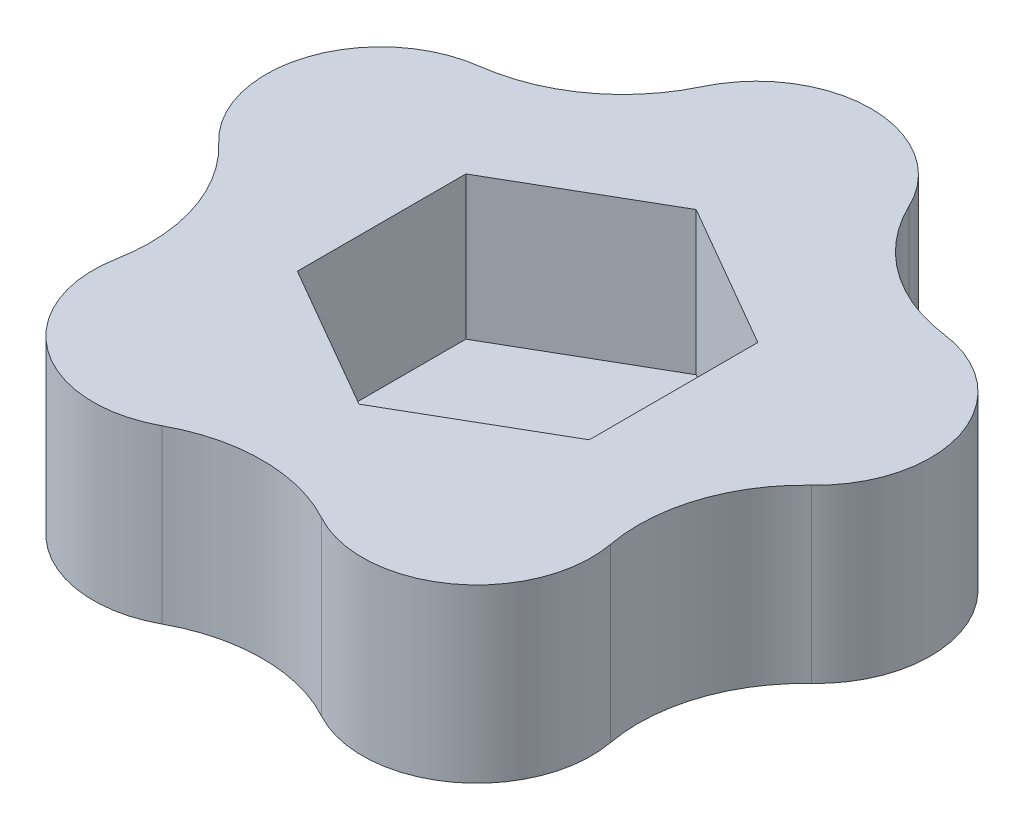
SolidWorks part; units mm, degrees
ref_plane "Front Plane" through (0, 0, 0) normal (0, 0, 1) x (1, 0, 0)
ref_plane "Top Plane" through (0, 0, 0) normal (0, 1, 0) x (1, 0, 0)
ref_plane "Right Plane" through (0, 0, 0) normal (1, 0, 0) x (0, 0, -1)
sketch "Sketch1" plane through (0, 0, 0) normal (0, 1, 0) x (1, 0, 0)
  line L0 (0, 0) -> (0, 8) construction
  line L1 (0, 8) -> (0, 13.848) construction
  line L2 (0, 5.889) -> (-5.1, 2.9445) construction
  line L3 (-5.1, 2.9445) -> (-5.1, -2.9445) construction
  line L4 (-5.1, -2.9445) -> (0, -5.889) construction
  line L5 (0, -5.889) -> (5.1, -2.9445) construction
  line L6 (5.1, -2.9445) -> (5.1, 2.9445) construction
  line L7 (5.1, 2.9445) -> (0, 5.889) construction
  circle A0 centre (0, 0) radius 5.1 construction
  arc A1 (-3.6141, 9.7142) -> (3.6141, 9.7142) centre (0, 8) cw
  arc A2 (8.122, 6.439) -> (10.3556, -0.4353) centre (7.6085, 2.4721) cw
  arc A3 (8.6337, -5.7347) -> (2.786, -9.9833) centre (4.7023, -6.4721) cw
  arc A4 (-2.786, -9.9833) -> (-8.6337, -5.7347) centre (-4.7023, -6.4721) cw
  arc A5 (-10.3556, -0.4353) -> (-8.122, 6.439) centre (-7.6085, 2.4721) cw
  arc A6 (-3.6141, 9.7142) -> (-8.122, 6.439) centre (-8.8686, 12.2066) cw
  arc A7 (8.122, 6.439) -> (3.6141, 9.7142) centre (8.8686, 12.2066) cw
  arc A8 (8.6337, -5.7347) -> (10.3556, -0.4353) centre (14.3497, -4.6625) cw
  arc A9 (-2.786, -9.9833) -> (2.786, -9.9833) centre (0, -15.0882) cw
  arc A10 (-10.3556, -0.4353) -> (-8.6337, -5.7347) centre (-14.3497, -4.6625) cw
  point P14 (0, 0)
  point P18 (0, 7.2098)
  point P28 (0, 0)
  point P41 (0, 0)
  dimension "D4" = 4
  dimension "D1" = 10.2
  dimension "D5" = 8
  dimension "D2" = 5
  dimension "D3" = 5
extrude "Boss-Extrude1" add sketch "Sketch1" along normal blind 6
sketch "Sketch2" plane through (0, 6, 0) normal (0, 1, 0) x (1, 0, 0)
  line L0 (-5.1, 2.9445) -> (-5.1, -2.9445) construction
  line L1 (-5.1, -2.9445) -> (0, -5.889) construction
  line L2 (0, -5.889) -> (5.1, -2.9445) construction
  line L3 (5.1, -2.9445) -> (5.1, 2.9445) construction
  line L4 (5.1, 2.9445) -> (0, 5.889) construction
  line L5 (0, 5.889) -> (-5.1, 2.9445) construction
  line L6 (-5.1, 2.9445) -> (-5.1, -2.9445)
  line L7 (-5.1, -2.9445) -> (0, -5.889)
  line L8 (0, -5.889) -> (5.1, -2.9445)
  line L9 (5.1, -2.9445) -> (5.1, 2.9445)
  line L10 (5.1, 2.9445) -> (0, 5.889)
  line L11 (0, 5.889) -> (-5.1, 2.9445)
  point P0 (0, 0)
extrude "Cut-Extrude1" cut sketch "Sketch2" against normal offset from surface (5 mm away) 1 up to face at (0, 0, 0)
